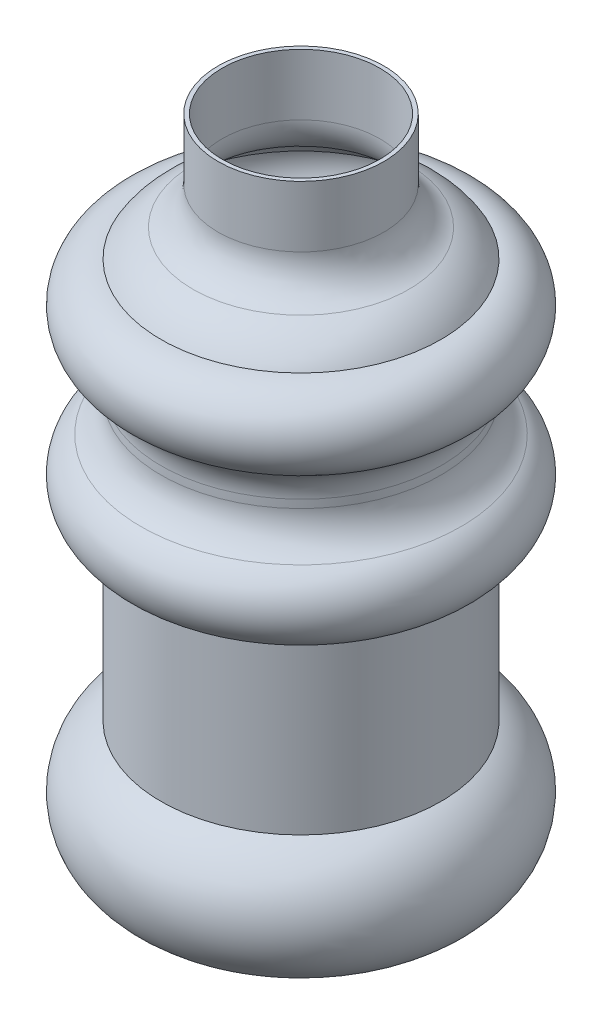
SolidWorks part; units mm, degrees
material "PET"
ref_plane "Alzado" through (0, 0, 0) normal (0, 0, 1) x (1, 0, 0)
ref_plane "Planta" through (0, 0, 0) normal (0, 1, 0) x (1, 0, 0)
ref_plane "Vista lateral" through (0, 0, 0) normal (1, 0, 0) x (0, 0, -1)
sketch "Croquis1" plane through (0, 0, 0) normal (0, 0, 1) x (1, 0, 0)
  line L0 (0, 0) -> (-85, 0)
  line L1 (-135, 420) -> (-135, 0) construction
  line L3 (-105, 285.8258) -> (-105, 335.8258)
  line L4 (-135, 420) -> (-62.1861, 420) construction
  line L5 (0, 0) -> (0, 420) construction
  line L6 (0, 420) -> (-62.1861, 420)
  line L7 (0, 0) -> (0, 420)
  line L8 (-105, 225.8258) -> (-105, 95.8258)
  arc A0 (-85, 0) -> (-105, 95.8258) centre (-85, 50) cw
  arc A1 (-105, 225.8258) -> (-105, 285.8258) centre (-105, 255.8258) cw
  arc A2 (-105, 335.8258) -> (-105, 395.8258) centre (-105, 365.8258) cw
  arc A3 (-105, 395.8258) -> (-62.1861, 420) centre (-62.1861, 370) cw
  point P4 (-105, 267.7443)
  dimension "D3" = 50
  dimension "D5" = 30
  dimension "D7" = 30
  dimension "D8" = 50
  dimension "D1" = 135
  dimension "D2" = 130
  dimension "D4" = 420
  dimension "D6" = 50
revolve "Revolución1" add sketch "Croquis1" angle 360 about L7
sketch "Croquis2" plane through (0, 420, 0) normal (0, 1, 0) x (1, 0, 0)
  circle A0 centre (0, 0) radius 62.1861 construction
  circle A1 centre (0, 0) radius 62.1861
extrude "Saliente-Extruir1" add sketch "Croquis2" along normal blind 70
fillet "Redondeo1" radius 30 3 edges at (0, 420, 62.1861) (0, 335.8258, -105) (0, 285.8258, -105)
shell "Vaciado1" thickness 3
